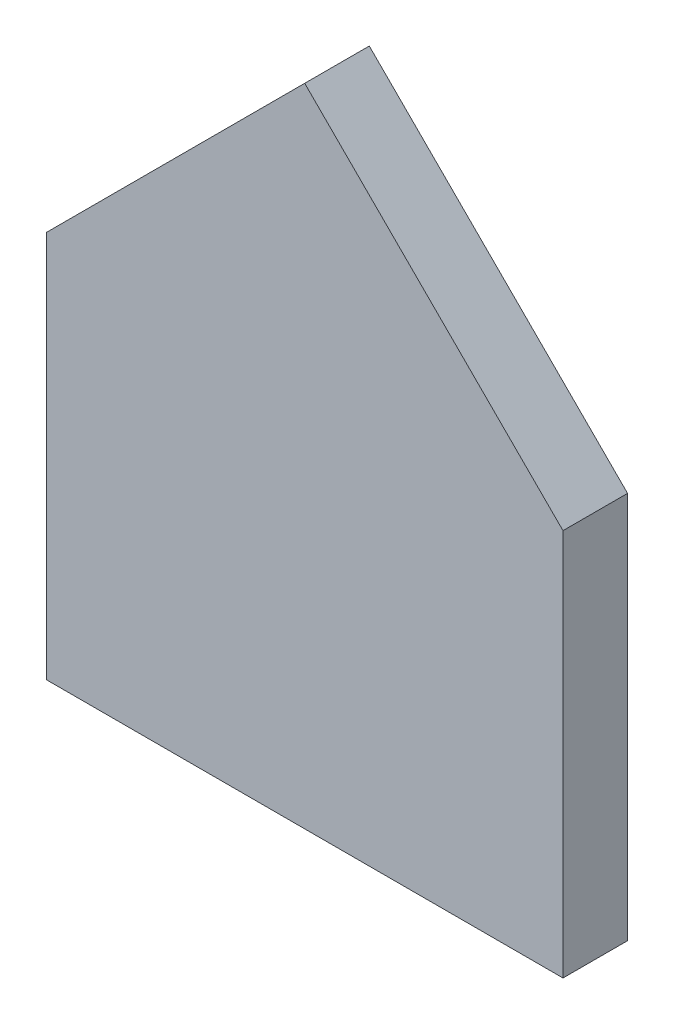
SolidWorks part; units mm, degrees
ref_plane "Plan de face" through (0, 0, 0) normal (0, 0, 1) x (1, 0, 0)
ref_plane "Plan de dessus" through (0, 0, 0) normal (0, 1, 0) x (1, 0, 0)
ref_plane "Plan de droite" through (0, 0, 0) normal (1, 0, 0) x (0, 0, -1)
sketch "Esquisse1" plane through (0, 0, 0) normal (0, 0, 1) x (1, 0, 0)
  line L0 (-40, -50) -> (-40, 10)
  line L1 (-40, -50) -> (40, -50)
  line L2 (-40, -50) -> (-40, 50) construction
  line L3 (-40, 50) -> (40, 50) construction
  line L4 (40, -50) -> (40, 50) construction
  line L5 (-40, -50) -> (40, 50) construction
  line L6 (-40, 50) -> (40, -50) construction
  line L7 (-40, 10) -> (0, 50)
  line L8 (0, 50) -> (40, 10)
  line L9 (40, 10) -> (40, -50)
  point P0 (0, 0)
  dimension "D1" = 100
  dimension "D2" = 80
  dimension "D3" = 60
  dimension "D4" = 45
  dimension "D5" = 45
extrude "Boss.-Extru.1" add sketch "Esquisse1" along normal blind 10
